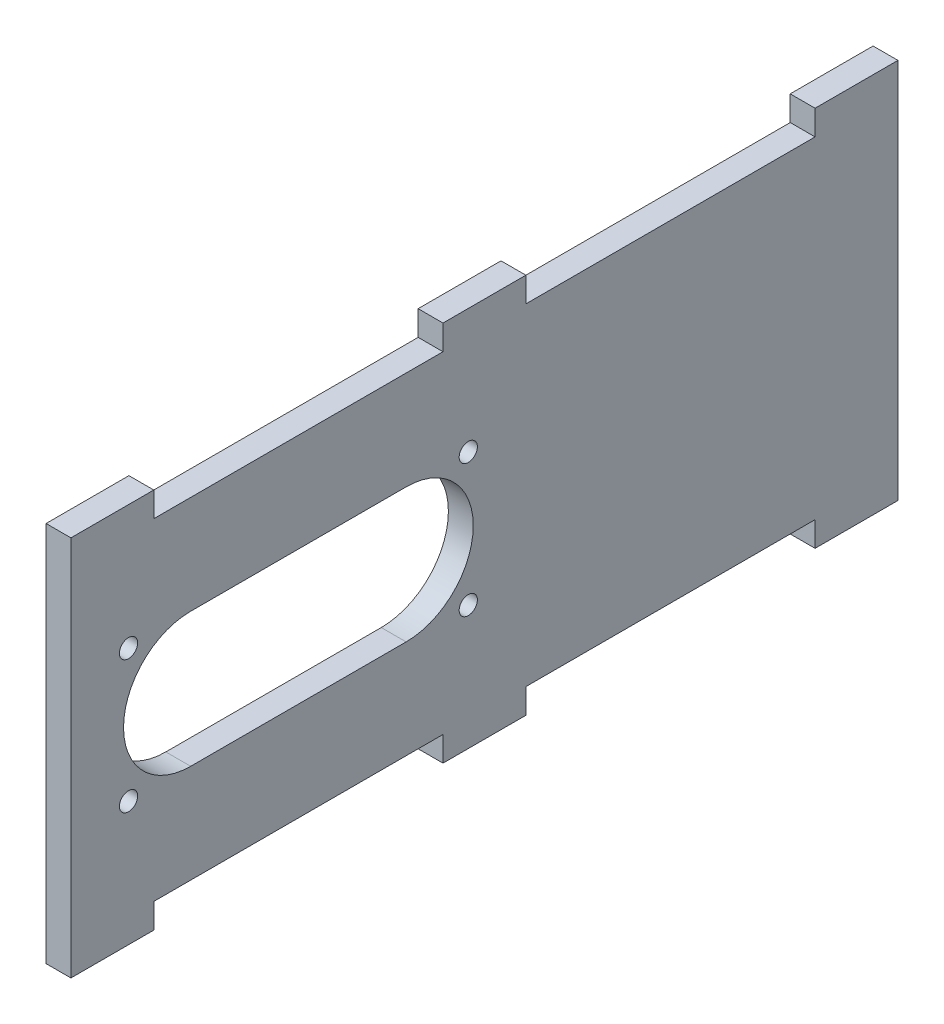
SolidWorks part; units mm, degrees
ref_plane "Front Plane" through (0, 0, 0) normal (0, 0, 1) x (1, 0, 0)
ref_plane "Top Plane" through (0, 0, 0) normal (0, 1, 0) x (1, 0, 0)
ref_plane "Right Plane" through (0, 0, 0) normal (1, 0, 0) x (0, 0, -1)
sketch "Sketch1" plane through (0, 0, 0) normal (1, 0, 0) x (0, 0, -1)
  line L0 (17.45, 20) -> (17.45, 23)
  line L1 (-27.45, 20) -> (72.35, 20)
  line L2 (-27.45, 20) -> (-27.45, -20)
  line L3 (-27.45, -20) -> (72.35, -20)
  line L4 (72.35, 20) -> (72.35, -20)
  line L5 (-27.45, 20) -> (-17.45, 20)
  line L6 (-27.45, 20) -> (-27.45, 23)
  line L7 (-27.45, 23) -> (-17.45, 23)
  line L8 (-17.45, 20) -> (-17.45, 23)
  line L9 (17.45, 20) -> (27.45, 20)
  line L10 (27.45, 20) -> (27.45, 23)
  line L11 (17.45, 23) -> (27.45, 23)
  line L12 (62.35, 20) -> (62.35, 23)
  line L13 (62.35, 20) -> (72.35, 20)
  line L14 (72.35, 20) -> (72.35, 23)
  line L15 (62.35, 23) -> (72.35, 23)
  line L16 (-17.45, 23) -> (17.45, 23) construction
  line L17 (27.45, 23) -> (62.35, 23) construction
  line L18 (-27.45, 0) -> (72.35, 0) construction
  line L19 (62.35, -20) -> (72.35, -20)
  line L20 (72.35, -20) -> (72.35, -23)
  line L21 (62.35, -23) -> (72.35, -23)
  line L22 (62.35, -20) -> (62.35, -23)
  line L23 (17.45, -20) -> (27.45, -20)
  line L24 (27.45, -20) -> (27.45, -23)
  line L25 (17.45, -23) -> (27.45, -23)
  line L26 (17.45, -20) -> (17.45, -23)
  line L27 (-27.45, -23) -> (-17.45, -23)
  line L28 (-17.45, -20) -> (-17.45, -23)
  line L29 (-27.45, -20) -> (-17.45, -20)
  line L30 (-27.45, -20) -> (-27.45, -23)
  point P7 (0, 23)
  point P8 (-27.45, 0)
  point P30 (-22.45, 23)
  point P31 (22.45, 23)
  dimension "D1" = 10
  dimension "D2" = 3
  dimension "D4" = 44.9
  dimension "D5" = 40
  dimension "D3" = 3
extrude "Boss-Extrude1" add sketch "Sketch1" along normal blind 3 contours L4 L1 L2 L3 | L1 L8 L7 L6 | L11 L0 L1 L10 | L15 L12 L1 L14 | L3 L22 L21 L20 | L3 L26 L25 L24 | L3 L30 L27 L28
sketch "Sketch2" plane through (3, 0, 0) normal (1, 0, 0) x (0, 0, -1)
  line L0 (22.45, 23) -> (22.45, -23) construction
  line L1 (17.45, 23) -> (27.45, 23) construction
  line L2 (17.45, -23) -> (27.45, -23) construction
  line L3 (-22.45, 23) -> (-22.45, -23) construction
  line L4 (-27.45, 23) -> (-17.45, 23) construction
  line L5 (-27.45, -23) -> (-17.45, -23) construction
  line L6 (-22.45, 0) -> (22.45, 0) construction
  point P14 (0, 0)
  line B0 (-13, 8.1) -> (13, 8.1)
  line B1 (-13, -8.1) -> (13, -8.1)
  arc B2 (-13, 8.1) -> (-13, -8.1) centre (-13, 0) ccw
  arc B3 (13, -8.1) -> (13, 8.1) centre (13, 0) ccw
  circle B4 centre (-20.5, 8) radius 1.1
  circle B5 centre (-20.5, -8) radius 1.1
  circle B6 centre (20.5, 8) radius 1.1
  circle B7 centre (20.5, -8) radius 1.1
sketch_block_instance "Block-SRF05-1"
sketch_block "Block-SRF05" parameters "D4"=16.2, "D5"=2.2, "D1"=45, "D2"=20, "D3"=26, "D6"=2, "D7"=2, "D8"=2, "D9"=2
extrude "Cut-Extrude1" cut sketch "Sketch2" against normal through all
